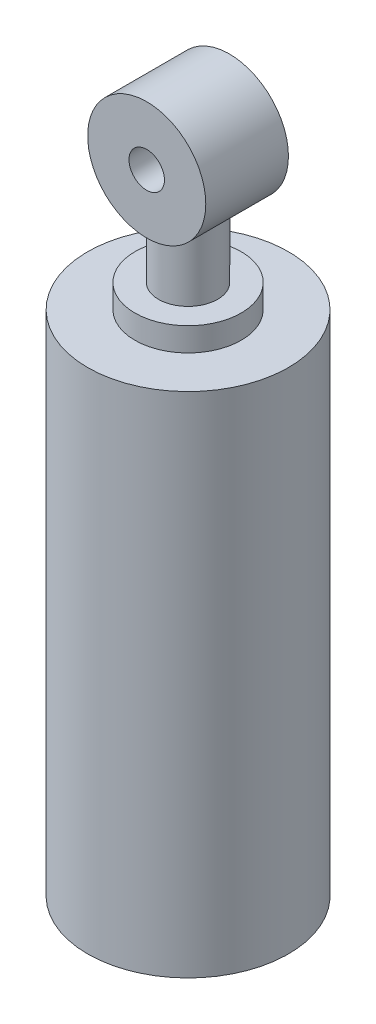
SolidWorks part; units mm, degrees
ref_plane "前视基准面" through (0, 0, 0) normal (0, 0, 1) x (1, 0, 0)
ref_plane "上视基准面" through (0, 0, 0) normal (0, 1, 0) x (1, 0, 0)
ref_plane "右视基准面" through (0, 0, 0) normal (1, 0, 0) x (0, 0, -1)
sketch "草图1" plane through (0, 0, 0) normal (0, 1, 0) x (1, 0, 0)
  circle A0 centre (0, 0) radius 8.5
  dimension "D1" = 17
extrude "凸台-拉伸1" add sketch "草图1" along normal blind 43
sketch "草图2" plane through (0, 0, 0) normal (0, 0, 1) x (1, 0, 0)
  line L0 (8.5, 43) -> (-8.5, 43) construction
  circle A0 centre (0, 55) radius 5
  dimension "D1" = 10
  dimension "D2" = 12
extrude "凸台-拉伸2" add sketch "草图2" along normal mid plane 7 separate body
sketch "草图3" plane through (0, 43, 0) normal (0, 1, 0) x (1, 0, 0)
  circle A0 centre (0, 0) radius 2.5
  dimension "D1" = 5
extrude "凸台-拉伸3" add sketch "草图3" along normal blind 9
sketch "草图4" plane through (0, 0, 3.5) normal (0, 0, 1) x (1, 0, 0)
  circle A0 centre (0, 55) radius 1.5
  dimension "D1" = 3
extrude "切除-拉伸1" cut sketch "草图4" against normal blind 10 contours A0
sketch "草图5" plane through (0, 43, 0) normal (0, 1, 0) x (1, 0, 0)
  circle A0 centre (0, 0) radius 4.5
  circle A1 centre (0, 0) radius 2.5
  dimension "D1" = 9
  dimension "D2" = 5
extrude "凸台-拉伸4" add sketch "草图5" along normal blind 2
